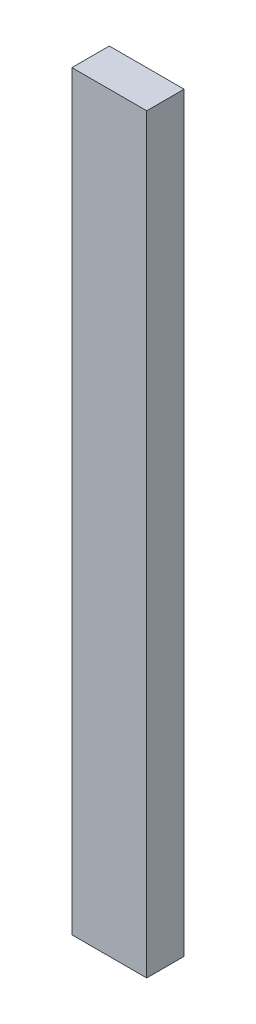
SolidWorks part; units mm, degrees
material "Sapin"
ref_plane "Plan de face" through (0, 0, 0) normal (0, 0, 1) x (1, 0, 0)
ref_plane "Plan de dessus" through (0, 0, 0) normal (0, 1, 0) x (1, 0, 0)
ref_plane "Plan de droite" through (0, 0, 0) normal (1, 0, 0) x (0, 0, -1)
sketch "Esquisse1" plane through (0, 0, 0) normal (0, 0, 1) x (1, 0, 0)
  line L1 (-24, -241) -> (24, -241)
  line L2 (-24, -241) -> (-24, 241)
  line L3 (-24, 241) -> (24, 241)
  line L4 (24, -241) -> (24, 241)
  line L5 (-24, -241) -> (24, 241) construction
  line L6 (-24, 241) -> (24, -241) construction
  point P0 (0, 0)
  dimension "D1" = 48
  dimension "D2" = 482
extrude "Boss.-Extru.1" add sketch "Esquisse1" along normal blind 24
